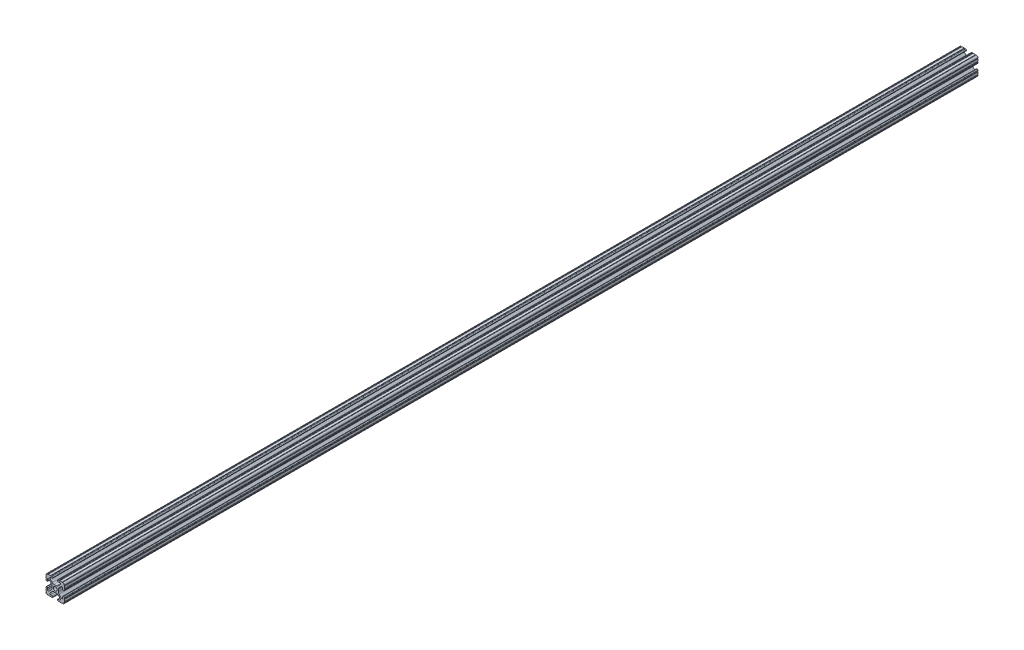
SolidWorks part; units mm, degrees
ref_plane "Front Plane" through (0, 0, 0) normal (0, 0, 1) x (1, 0, 0)
ref_plane "Top Plane" through (0, 0, 0) normal (0, 1, 0) x (1, 0, 0)
ref_plane "Right Plane" through (0, 0, 0) normal (1, 0, 0) x (0, 0, -1)
sketch "Sketch1" plane through (0, 0, 0) normal (0, 0, 1) x (1, 0, 0)
  line L0 (-7.207, 8.7244) -> (-3.8983, 5.4232)
  line L1 (-4.2875, 10.4902) -> (-6.4768, 10.4902)
  line L2 (-3.2385, 11.651) -> (-3.2385, 11.5392)
  line L3 (-5.3171, 12.7) -> (-4.2875, 12.7)
  line L4 (0, 13.4005) -> (0, -14.8534) construction
  line L5 (12.7, 0) -> (-13.9989, 0) construction
  line L6 (-9.5504, 12.7) -> (-6.3331, 12.7)
  line L7 (-12.7, 6.3331) -> (-12.7, 9.5504)
  line L8 (-12.7, 4.2875) -> (-12.7, 5.3171)
  line L9 (-11.5392, 3.2385) -> (-11.651, 3.2385)
  line L10 (-10.4902, 6.4021) -> (-10.4902, 4.2875)
  line L11 (-5.441, 3.8408) -> (-8.7371, 7.1294)
  line L12 (-4.5085, -1.5932) -> (-4.5085, 1.5932)
  line L13 (-1.7093, -4.4958) -> (1.7093, -4.4958)
  line L14 (3.9523, -5.4237) -> (7.1797, -8.6452)
  line L15 (6.4164, -10.4902) -> (4.2875, -10.4902)
  line L16 (3.2385, -11.5392) -> (3.2385, -11.651)
  line L17 (4.2875, -12.7) -> (5.3171, -12.7)
  line L18 (6.3331, -12.7) -> (9.5504, -12.7)
  line L19 (12.7, -9.5504) -> (12.7, -6.3331)
  line L20 (12.7, -5.3171) -> (12.7, -4.2875)
  line L21 (11.651, -3.2385) -> (11.5392, -3.2385)
  line L22 (10.4902, -4.2875) -> (10.4902, -6.4021)
  line L23 (8.7371, -7.1294) -> (5.441, -3.8408)
  line L24 (4.5085, -1.5932) -> (4.5085, 1.5932)
  line L25 (5.441, 3.8408) -> (8.7371, 7.1294)
  line L26 (10.4902, 6.4021) -> (10.4902, 4.2875)
  line L27 (11.5392, 3.2385) -> (11.651, 3.2385)
  line L28 (12.7, 4.2875) -> (12.7, 5.3171)
  line L29 (12.7, 6.3331) -> (12.7, 9.5504)
  line L30 (9.5504, 12.7) -> (6.3331, 12.7)
  line L31 (5.3171, 12.7) -> (4.2875, 12.7)
  line L32 (3.2385, 11.651) -> (3.2385, 11.5392)
  line L33 (4.2875, 10.4902) -> (6.4768, 10.4902)
  line L34 (7.207, 8.7244) -> (3.8983, 5.4232)
  line L35 (1.6558, 4.4958) -> (-1.6558, 4.4958)
  line L36 (-8.7371, -7.1294) -> (-5.441, -3.8408)
  line L37 (-10.4902, -4.2875) -> (-10.4902, -6.4021)
  line L38 (-11.651, -3.2385) -> (-11.5392, -3.2385)
  line L39 (-12.7, -5.3171) -> (-12.7, -4.2875)
  line L40 (-12.7, -9.5504) -> (-12.7, -6.3331)
  line L41 (-6.3331, -12.7) -> (-9.5504, -12.7)
  line L42 (-4.2875, -12.7) -> (-5.3171, -12.7)
  line L43 (-3.2385, -11.5392) -> (-3.2385, -11.651)
  line L44 (-6.4164, -10.4902) -> (-4.2875, -10.4902)
  line L45 (-3.9523, -5.4237) -> (-7.1797, -8.6452)
  arc A0 (-7.207, 8.7244) -> (-6.4768, 10.4902) centre (-6.4768, 9.4563) cw
  arc A1 (-3.2385, 11.5392) -> (-4.2875, 10.4902) centre (-4.2875, 11.5392) cw
  arc A2 (-4.2875, 12.7) -> (-3.2385, 11.651) centre (-4.2875, 11.651) cw
  arc A3 (-5.3171, 12.7) -> (-6.3331, 12.7) centre (-5.8251, 12.7) cw
  arc A4 (-9.5504, 12.7) -> (-10.5664, 12.6998) centre (-10.0584, 12.7) cw
  arc A5 (-12.6998, 10.5664) -> (-10.5664, 12.6998) centre (-10.5918, 10.5918) cw
  arc A6 (-12.6998, 10.5664) -> (-12.7, 9.5504) centre (-12.7, 10.0584) cw
  arc A7 (-12.7, 6.3331) -> (-12.7, 5.3171) centre (-12.7, 5.8251) cw
  arc A8 (-11.651, 3.2385) -> (-12.7, 4.2875) centre (-11.651, 4.2875) cw
  arc A9 (-10.4902, 4.2875) -> (-11.5392, 3.2385) centre (-11.5392, 4.2875) cw
  circle A10 centre (0, 0) radius 2.6035
  arc A11 (-10.4902, 6.4021) -> (-8.7371, 7.1294) centre (-9.4628, 6.4021) cw
  arc A12 (-5.441, 3.8408) -> (-4.5085, 1.5932) centre (-7.6835, 1.5932) cw
  arc A13 (-4.5085, -1.5932) -> (-5.441, -3.8408) centre (-7.6835, -1.5932) cw
  arc A14 (-8.7371, -7.1294) -> (-10.4902, -6.4021) centre (-9.4628, -6.4021) cw
  arc A15 (-1.7093, -4.4958) -> (-3.9523, -5.4237) centre (-1.7093, -7.6708) ccw
  arc A16 (3.9523, -5.4237) -> (1.7093, -4.4958) centre (1.7093, -7.6708) ccw
  arc A17 (6.4164, -10.4902) -> (7.1797, -8.6452) centre (6.4164, -9.4098) ccw
  arc A18 (4.2875, -10.4902) -> (3.2385, -11.5392) centre (4.2875, -11.5392) ccw
  arc A19 (3.2385, -11.651) -> (4.2875, -12.7) centre (4.2875, -11.651) ccw
  arc A20 (6.3331, -12.7) -> (5.3171, -12.7) centre (5.8251, -12.7) ccw
  arc A21 (10.5664, -12.6998) -> (9.5504, -12.7) centre (10.0584, -12.7) ccw
  arc A22 (10.5664, -12.6998) -> (12.6998, -10.5664) centre (10.5918, -10.5918) ccw
  arc A23 (12.7, -9.5504) -> (12.6998, -10.5664) centre (12.7, -10.0584) ccw
  arc A24 (12.7, -5.3171) -> (12.7, -6.3331) centre (12.7, -5.8251) ccw
  arc A25 (12.7, -4.2875) -> (11.651, -3.2385) centre (11.651, -4.2875) ccw
  arc A26 (11.5392, -3.2385) -> (10.4902, -4.2875) centre (11.5392, -4.2875) ccw
  arc A27 (8.7371, -7.1294) -> (10.4902, -6.4021) centre (9.4628, -6.4021) ccw
  arc A28 (4.5085, -1.5932) -> (5.441, -3.8408) centre (7.6835, -1.5932) ccw
  arc A29 (5.441, 3.8408) -> (4.5085, 1.5932) centre (7.6835, 1.5932) ccw
  arc A30 (10.4902, 6.4021) -> (8.7371, 7.1294) centre (9.4628, 6.4021) ccw
  arc A31 (10.4902, 4.2875) -> (11.5392, 3.2385) centre (11.5392, 4.2875) ccw
  arc A32 (11.651, 3.2385) -> (12.7, 4.2875) centre (11.651, 4.2875) ccw
  arc A33 (12.7, 6.3331) -> (12.7, 5.3171) centre (12.7, 5.8251) ccw
  arc A34 (12.6998, 10.5664) -> (12.7, 9.5504) centre (12.7, 10.0584) ccw
  arc A35 (12.6998, 10.5664) -> (10.5664, 12.6998) centre (10.5918, 10.5918) ccw
  arc A36 (9.5504, 12.7) -> (10.5664, 12.6998) centre (10.0584, 12.7) ccw
  arc A37 (5.3171, 12.7) -> (6.3331, 12.7) centre (5.8251, 12.7) ccw
  arc A38 (4.2875, 12.7) -> (3.2385, 11.651) centre (4.2875, 11.651) ccw
  arc A39 (3.2385, 11.5392) -> (4.2875, 10.4902) centre (4.2875, 11.5392) ccw
  arc A40 (7.207, 8.7244) -> (6.4768, 10.4902) centre (6.4768, 9.4563) ccw
  arc A41 (1.6558, 4.4958) -> (3.8983, 5.4232) centre (1.6558, 7.6708) ccw
  arc A42 (-1.6558, 4.4958) -> (-3.8983, 5.4232) centre (-1.6558, 7.6708) cw
  arc A43 (-11.5392, -3.2385) -> (-10.4902, -4.2875) centre (-11.5392, -4.2875) cw
  arc A44 (-12.7, -4.2875) -> (-11.651, -3.2385) centre (-11.651, -4.2875) cw
  arc A45 (-12.7, -5.3171) -> (-12.7, -6.3331) centre (-12.7, -5.8251) cw
  arc A46 (-12.7, -9.5504) -> (-12.6998, -10.5664) centre (-12.7, -10.0584) cw
  arc A47 (-10.5664, -12.6998) -> (-12.6998, -10.5664) centre (-10.5918, -10.5918) cw
  arc A48 (-10.5664, -12.6998) -> (-9.5504, -12.7) centre (-10.0584, -12.7) cw
  arc A49 (-6.3331, -12.7) -> (-5.3171, -12.7) centre (-5.8251, -12.7) cw
  arc A50 (-3.2385, -11.651) -> (-4.2875, -12.7) centre (-4.2875, -11.651) cw
  arc A51 (-4.2875, -10.4902) -> (-3.2385, -11.5392) centre (-4.2875, -11.5392) cw
  arc A52 (-6.4164, -10.4902) -> (-7.1797, -8.6452) centre (-6.4164, -9.4098) cw
  dimension "D1" = 5.207
  dimension "D9" = 14.859
  dimension "D2" = 25.4
  dimension "D3" = 12.7
  dimension "D4" = 6.477
  dimension "D5" = 8.2042
  dimension "D6" = 9.017
  dimension "D8" = 2.2098
  dimension "D10" = 2.2098
extrude "Extrude1" add sketch "Sketch1" against normal blind 1270
